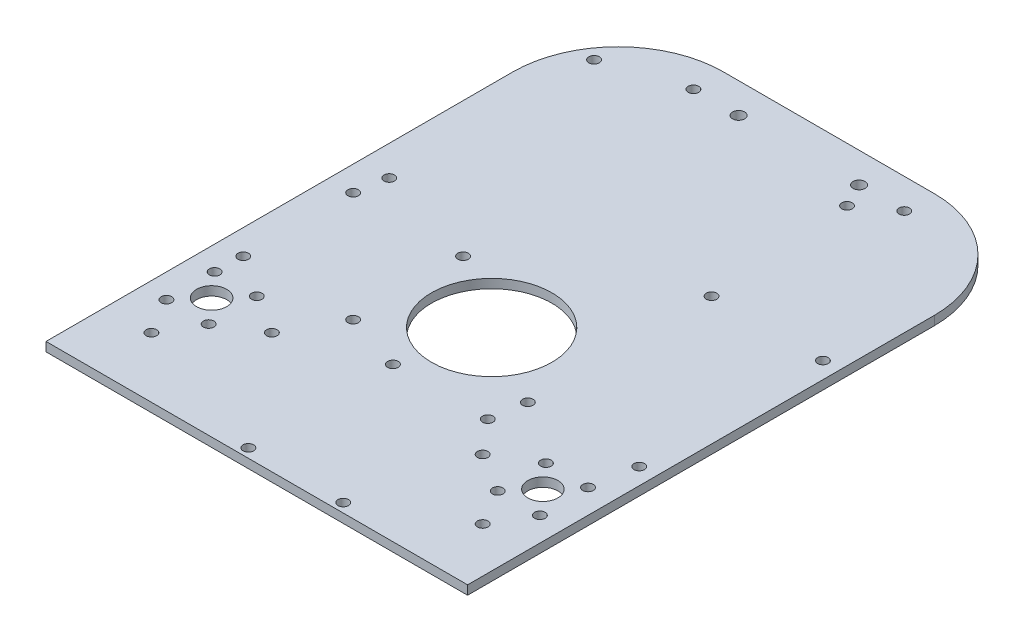
SolidWorks part; units mm, degrees
ref_plane "前视基准面" through (0, 0, 0) normal (0, 0, 1) x (1, 0, 0)
ref_plane "上视基准面" through (0, 0, 0) normal (0, 1, 0) x (1, 0, 0)
ref_plane "右视基准面" through (0, 0, 0) normal (1, 0, 0) x (0, 0, -1)
sketch "草图1" plane through (0, 0, 0) normal (0, 1, 0) x (1, 0, 0)
  line L0 (0, -110) -> (0, -83) construction
  line L1 (-70, 110) -> (70, 110)
  line L2 (-70, 110) -> (-70, -110)
  line L3 (-70, -110) -> (70, -110)
  line L4 (70, 110) -> (70, -110)
  line L5 (-70, 110) -> (70, -110) construction
  line L6 (-70, -110) -> (70, 110) construction
  line L7 (0, -83) -> (9.95, -83) construction
  line L8 (0, 0) -> (0, -32) construction
  line L9 (-5.8, -59) -> (25.7, -59) construction
  line L10 (-5.8, -59) -> (-5.8, -107) construction
  line L11 (-5.8, -107) -> (25.7, -107) construction
  line L12 (25.7, -59) -> (25.7, -107) construction
  line L13 (-5.8, -59) -> (25.7, -107) construction
  line L14 (-5.8, -107) -> (25.7, -59) construction
  line L15 (-70, 80) -> (70, 80) construction
  circle A1 centre (-5.8, -59) radius 1.75
  circle A2 centre (25.7, -59) radius 1.75
  circle A3 centre (-5.8, -107) radius 1.75
  circle A4 centre (25.7, -107) radius 1.75
  circle A5 centre (0, -32) radius 20
  point P0 (0, 0)
  dimension "D3" = 40
  dimension "D8" = 3.5
  dimension "D9" = 30
  dimension "D10" = 3.5
  dimension "D11" = 3.5
  dimension "D13" = 3.5
  dimension "D1" = 140
  dimension "D2" = 220
  dimension "D4" = 27
  dimension "D5" = 9.95
  dimension "D6" = 31.5
  dimension "D7" = 48
  dimension "D12" = 32
extrude "凸台-拉伸1" add sketch "草图1" along normal blind 3
sketch "草图2" plane through (0, 3, 0) normal (0, 1, 0) x (1, 0, 0)
  line L0 (-70, -110) -> (70, -110) construction
  line L1 (70, -110) -> (70, 110) construction
  line L2 (-70, 0) -> (70, 0) construction
  line L3 (-70, 110) -> (-70, -110) construction
  line L4 (0, 110) -> (0, -110) construction
  line L5 (70, 110) -> (-70, 110) construction
  line L6 (0, -70) -> (70, -70) construction
  line L7 (55, 0) -> (55, -110) construction
  line L8 (20, 70) -> (-20, 70) construction
  line L9 (35, 70) -> (-35, 70) construction
  line L10 (35, 70) -> (35, -70) construction
  line L11 (35, -70) -> (-35, -70) construction
  line L12 (-35, 70) -> (-35, -70) construction
  line L13 (35, 70) -> (-35, -70) construction
  line L14 (35, -70) -> (-35, 70) construction
  circle A4 centre (48, -62) radius 1.75
  circle A5 centre (62, -62) radius 1.75
  circle A6 centre (62, -78) radius 1.75
  circle A7 centre (48, -78) radius 1.75
  circle A8 centre (-62, -78) radius 1.75
  circle A9 centre (-48, -78) radius 1.75
  circle A10 centre (-62, -62) radius 1.75
  circle A11 centre (-48, -62) radius 1.75
  circle A23 centre (-35, 70) radius 1.75
  circle A24 centre (-35, -70) radius 1.75
  circle A25 centre (35, -70) radius 1.75
  circle A26 centre (35, 70) radius 1.75
  circle A27 centre (-20, 70) radius 2
  circle A28 centre (20, 70) radius 2
  circle A29 centre (55, -70) radius 5
  circle A30 centre (-55, -70) radius 5
  point P0 (55, -70)
  point P19 (0, 70)
  point P60 (0, 0)
  dimension "D3" = 15
  dimension "D4" = 3.5
  dimension "D5" = 10
  dimension "D6" = 3.5
  dimension "D7" = 3.5
  dimension "D12" = 4
  dimension "D14" = 3.5
  dimension "D17" = 3.5
  dimension "D18" = 3.5
  dimension "D19" = 3.5
  dimension "D20" = 3.5
  dimension "D21" = 3.5
  dimension "D11" = 3.5
  dimension "D2" = 3.5
  dimension "D16" = 3.5
  dimension "D8" = 14
  dimension "D9" = 16
  dimension "D10" = 40
  dimension "D13" = 140
  dimension "D15" = 70
extrude "切除-拉伸1" cut sketch "草图2" against normal through all
sketch "草图3" plane through (0, 3, 0) normal (0, 1, 0) x (1, 0, 0)
  line L0 (-55, -70) -> (-55, -90) construction
  line L5 (55, -70) -> (55, -90) construction
  line L8 (-20, 70) -> (20, 70) construction
  line L9 (0, 70) -> (0, 74) construction
  line L16 (-70, -110) -> (70, -110) construction
  circle A13 centre (55, -90) radius 1.75
  circle A15 centre (-55, -90) radius 1.75
  circle A24 centre (64.5, -47.5) radius 1.75
  circle A25 centre (27.5, -47.5) radius 1.75
  circle A26 centre (64.5, 13.5) radius 1.75
  circle A27 centre (27.5, 13.5) radius 1.75
  circle A29 centre (-25.25, -52.75) radius 1.75
  circle A30 centre (-61.75, -16.25) radius 1.75
  circle A31 centre (-25.25, -16.25) radius 1.75
  circle A33 centre (24, 62) radius 1.75 construction
  circle A34 centre (-60, 62) radius 1.75 construction
  circle A35 centre (-60, -6) radius 1.75
  circle A36 centre (24, 62) radius 1.75
  circle A37 centre (-60, 62) radius 1.75
  circle A38 centre (-61.75, -52.75) radius 1.75
  circle A42 centre (55, -70) radius 5 construction
  circle A43 centre (-55, -70) radius 5 construction
  circle A44 centre (55, -70) radius 5 construction
  circle A45 centre (-55, -70) radius 5 construction
  dimension "D3" = 3.5
  dimension "D4" = 3.5
  dimension "D5" = 3.5
  dimension "D6" = 20
  dimension "D11" = 3.5
  dimension "D12" = 3.5
  dimension "D13" = 3.5
  dimension "D19" = 20
  dimension "D2" = 3.5
  dimension "D7" = 3.5
  dimension "D8" = 3.5
  dimension "D9" = 3.5
  dimension "D10" = 3.5
  dimension "D15" = 4
extrude "切除-拉伸2" cut sketch "草图3" against normal through all
sketch "草图5" plane through (0, 3, 0) normal (0, 1, 0) x (1, 0, 0)
  line L0 (70, -110) -> (70, 110) construction
  line L1 (70, 110) -> (-70, 110) construction
  line L2 (-70, 110) -> (-70, -110) construction
  line L3 (70, -110) -> (70, 45) construction
  line L4 (70, 110) -> (-70, 110) construction
  line L5 (-70, 45) -> (-70, -110) construction
  line L6 (-35, 80) -> (35, 80)
  line L7 (-70, 110) -> (-70, 80) construction
  line L8 (70, 80) -> (70, 110) construction
  line L9 (-70, 45) -> (-70, 110)
  line L10 (-70, 110) -> (70, 110)
  line L11 (70, 110) -> (70, 45)
  arc A0 (-70, 45) -> (-35, 80) centre (-35, 45) cw
  arc A1 (70, 45) -> (35, 80) centre (35, 45) ccw
  dimension "D2" = 35
  dimension "D3" = 35
  dimension "D1" = 30
extrude "切除-拉伸3" cut sketch "草图5" against normal through all
